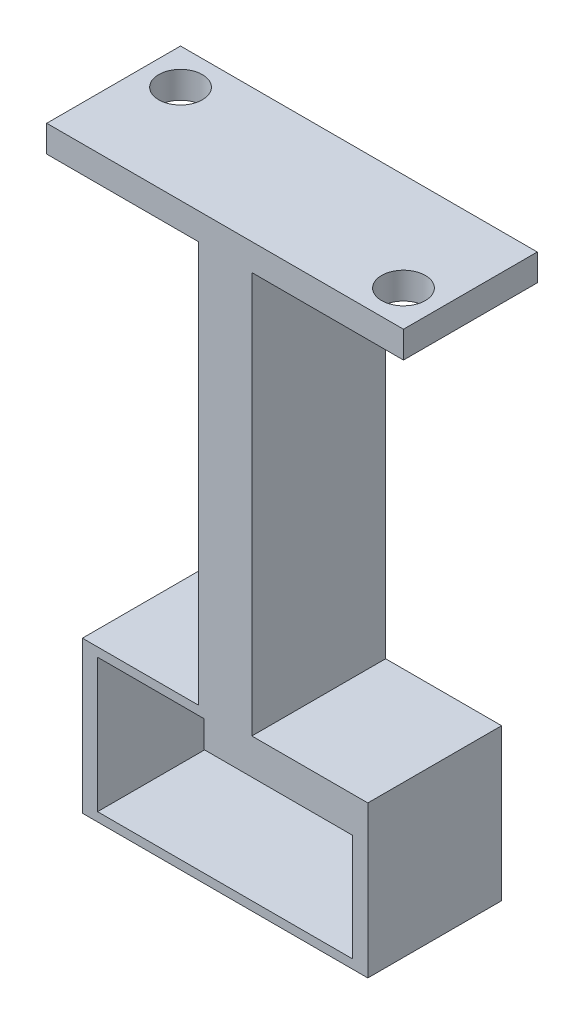
SolidWorks part; units mm, degrees
material "PA Tipo 6"
ref_plane "Plano frontal" through (0, 0, 0) normal (0, 0, 1) x (1, 0, 0)
ref_plane "Plano superior" through (0, 0, 0) normal (0, 1, 0) x (1, 0, 0)
ref_plane "Plano direito" through (0, 0, 0) normal (1, 0, 0) x (0, 0, -1)
sketch "Esboço1" plane through (0, 0, 0) normal (0, 0, 1) x (1, 0, 0)
  line L5 (-46.6147, 0.3541) -> (-14.6147, 0.3541)
  line L6 (-46.6147, 0.3541) -> (-46.6147, -16.6459)
  line L7 (-46.6147, -16.6459) -> (-14.6147, -16.6459)
  line L8 (-14.6147, 0.3541) -> (-14.6147, -16.6459)
  dimension "D1" = 32
  dimension "D2" = 17
extrude "Ressalto-extrusão1" add sketch "Esboço1" along normal blind 15
ref_plane "Plano1" through (0, 0.3541, 0) normal (0, 1, 0) x (1, 0, 0)
sketch "Esboço2" plane through (0, 0.3541, 0) normal (0, 1, 0) x (1, 0, 0)
  line L0 (-30.6147, 0) -> (-30.6147, -17.0117) construction
  line L1 (-14.6147, 0) -> (-46.6147, 0) construction
  line L2 (-33.6147, 0) -> (-27.6147, 0)
  line L3 (-33.6147, 0) -> (-33.6147, -15)
  line L4 (-33.6147, -15) -> (-27.6147, -15)
  line L5 (-27.6147, 0) -> (-27.6147, -15)
  dimension "D1" = 6
extrude "Ressalto-extrusão2" add sketch "Esboço2" along normal blind 45 and the other way blind 3
sketch "Esboço3" plane through (0, 45.3541, 0) normal (0, 1, 0) x (1, 0, 0)
  line L1 (-50.6147, 0) -> (-10.6147, 0)
  line L2 (-50.6147, 0) -> (-50.6147, -15)
  line L3 (-50.6147, -15) -> (-10.6147, -15)
  line L4 (-10.6147, 0) -> (-10.6147, -15)
  line L6 (-30.6147, 0) -> (-30.6147, -17.262) construction
  line L7 (-27.6147, 0) -> (-33.6147, 0) construction
  dimension "D1" = 40
extrude "Ressalto-extrusão3" add sketch "Esboço3" along normal blind 3
sketch "Esboço5" plane through (0, 48.3541, 0) normal (0, 1, 0) x (1, 0, 0)
  line L0 (-10.6147, -15) -> (-10.6147, 0) construction
  line L1 (-10.6147, -7.5) -> (-23.8723, -7.5) construction
  line L2 (-10.6147, -15) -> (-10.6147, 0) construction
  line L3 (-50.6147, 0) -> (-50.6147, -15) construction
  line L4 (-10.6147, 0) -> (-50.6147, 0) construction
  line L5 (-50.6147, -15) -> (-10.6147, -15) construction
  line L6 (-50.6147, -7.5) -> (-10.6147, -7.5) construction
  line L7 (-50.6147, 0) -> (-50.6147, -15) construction
  circle A0 centre (-46.6147, -4) radius 2.45
  circle A4 centre (-14.6147, -11) radius 2.45
  dimension "D1" = 4.9
  dimension "D2" = 4
  dimension "D3" = 4
  dimension "D4" = 4.9
  dimension "D5" = 4
  dimension "D6" = 4
extrude "Corte-extrusão1" cut sketch "Esboço5" against normal blind 6 and the other way through all
sketch "Esboço7" plane through (0, 0, 15) normal (0, 0, 1) x (1, 0, 0)
  line L0 (-44.9147, -15.6459) -> (-44.9147, -0.6459)
  line L1 (-44.9147, -0.6459) -> (-32.9725, -0.6459)
  line L2 (-32.9725, -0.6459) -> (-32.9725, -3.6459)
  line L3 (-32.9725, -3.6459) -> (-16.3147, -3.6459)
  line L4 (-16.3147, -3.6459) -> (-16.3147, -15.6459)
  line L5 (-16.3147, -15.6459) -> (-44.9147, -15.6459)
  line L6 (-33.6147, 0.3541) -> (-46.6147, 0.3541) construction
  line L7 (-46.6147, 0.3541) -> (-46.6147, -16.6459) construction
  line L8 (-14.6147, -16.6459) -> (-14.6147, 0.3541) construction
  line L9 (-46.6147, -16.6459) -> (-14.6147, -16.6459) construction
  dimension "D1" = 1
  dimension "D2" = 1.7
  dimension "D3" = 1.7
  dimension "D4" = 1
  dimension "D5" = 3
extrude "Corte-extrusão2" cut sketch "Esboço7" against normal blind 12
sketch "Esboço8" plane through (0, 0, 3) normal (0, 0, 1) x (1, 0, 0)
  circle A0 centre (-42.3647, -13.3959) radius 1
  circle A1 centre (-18.8647, -5.8959) radius 1
extrude "Corte-extrusão3" cut sketch "Esboço8" against normal through all both and the other way through all
sketch "Esboço9" plane through (0, 0, 0) normal (0, 0, -1) x (-1, 0, 0)
  line L0 (40.3647, -5.6459) -> (20.8647, -5.6459) construction
  line L1 (20.3647, -5.1459) -> (40.8647, -5.1459)
  line L2 (20.3647, -5.1459) -> (20.3647, -14.1459)
  line L3 (20.3647, -14.1459) -> (40.8647, -14.1459)
  line L4 (40.8647, -5.1459) -> (40.8647, -14.1459)
  line L5 (20.8647, -5.6459) -> (20.8647, -13.6459) construction
  line L6 (20.8647, -13.6459) -> (40.3647, -13.6459) construction
  line L7 (40.3647, -13.6459) -> (40.3647, -5.6459) construction
  dimension "D1" = 0.5
  dimension "D2" = 0.5
  dimension "D3" = 0.5
  dimension "D4" = 0.5
extrude "Corte-extrusão4" cut sketch "Esboço9" against normal through all both and the other way through all
